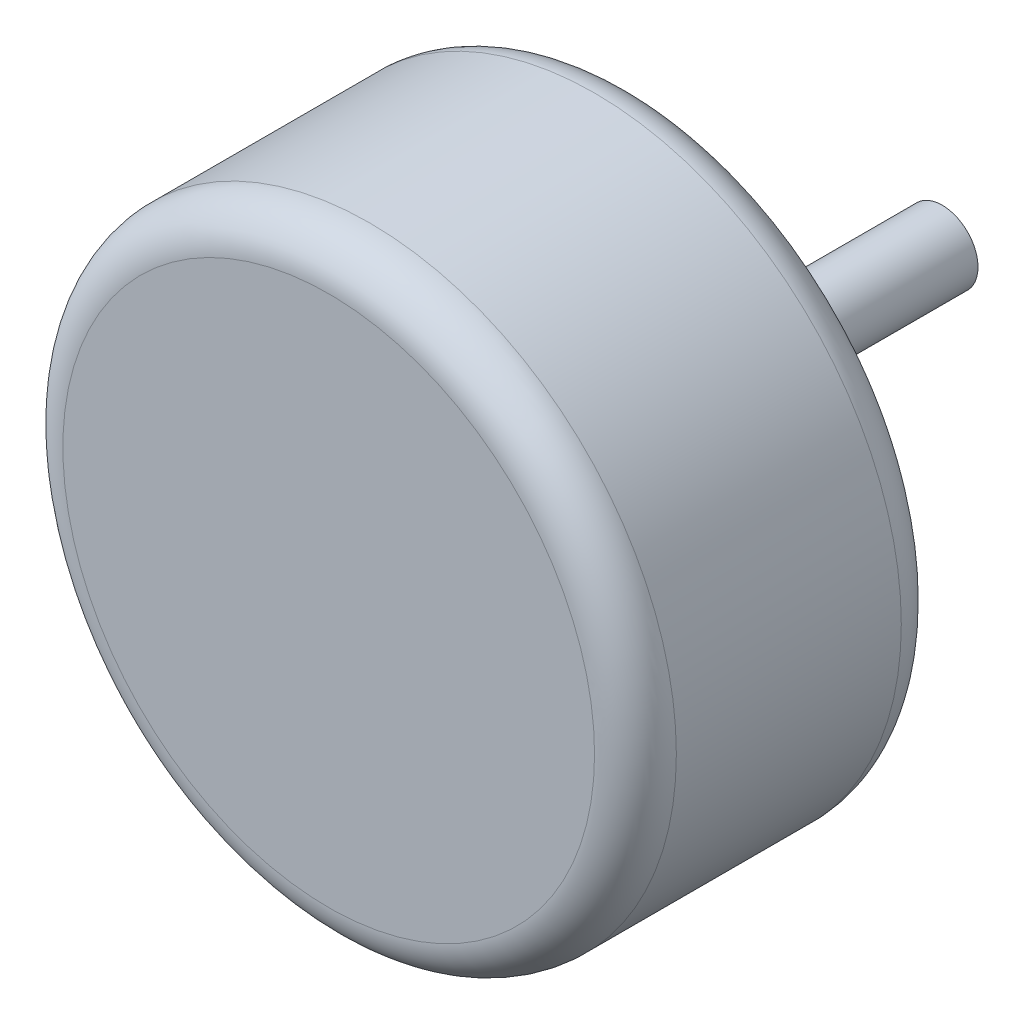
SolidWorks part; units mm, degrees
ref_plane "Front Plane" through (0, 0, 0) normal (0, 0, 1) x (1, 0, 0)
ref_plane "Top Plane" through (0, 0, 0) normal (0, 1, 0) x (1, 0, 0)
ref_plane "Right Plane" through (0, 0, 0) normal (1, 0, 0) x (0, 0, -1)
sketch "Sketch1" plane through (0, 0, 0) normal (0, 0, 1) x (1, 0, 0)
  circle A0 centre (0, 0) radius 76.2
  dimension "D1" = 152.4
extrude "Boss-Extrude1" add sketch "Sketch1" along normal blind 76.2
sketch "Sketch2" plane through (0, 0, 0) normal (0, 0, -1) x (-1, 0, 0)
  circle A0 centre (0, 0) radius 8.89
  dimension "D1" = 17.78
extrude "Boss-Extrude3" add sketch "Sketch2" along normal blind 76.2
fillet "Fillet1" radius 10.16 1 edges at (76.2, 0, 76.2)
fillet "Fillet2" radius 10.16 1 edges at (76.2, 0, 0)
